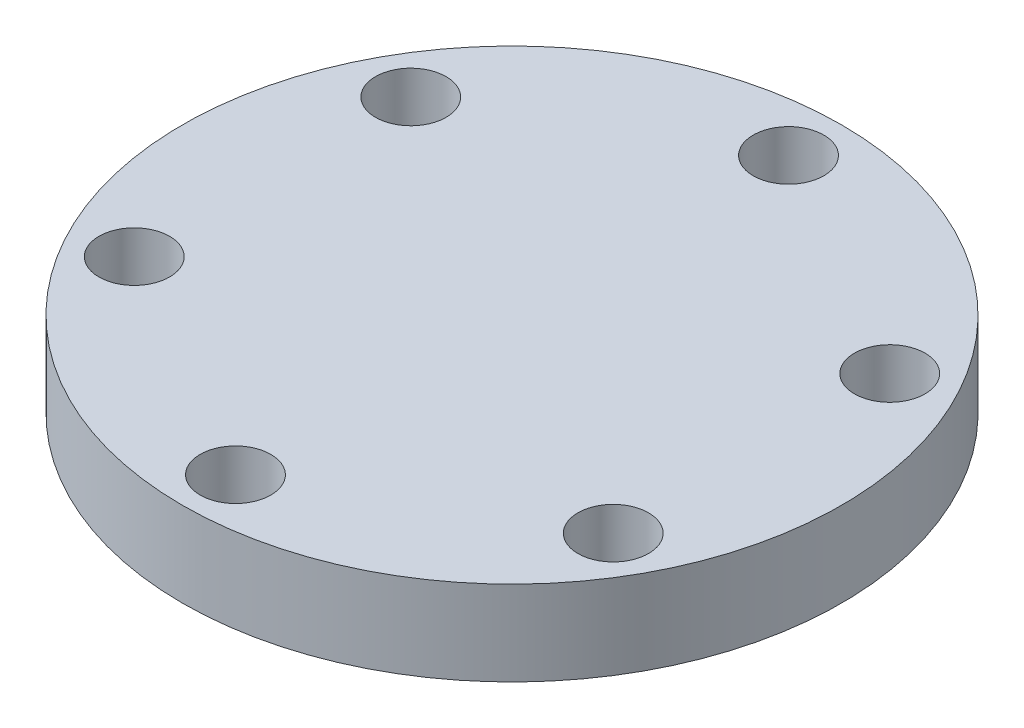
SolidWorks part; units mm, degrees
ref_plane "Front Plane" through (0, 0, 0) normal (0, 0, 1) x (1, 0, 0)
ref_plane "Top Plane" through (0, 0, 0) normal (0, 1, 0) x (1, 0, 0)
ref_plane "Right Plane" through (0, 0, 0) normal (1, 0, 0) x (0, 0, -1)
sketch "Sketch1" plane through (0, 0, 0) normal (0, 1, 0) x (1, 0, 0)
  circle A0 centre (0, 0) radius 7
  dimension "D1" = 14
extrude "Boss-Extrude1" add sketch "Sketch1" along normal blind 1.8
sketch "Sketch2" plane through (0, 0, 0) normal (0, -1, 0) x (1, 0, 0)
  circle A0 centre (0, 5.8737) radius 0.75
  dimension "D1" = 1.5
extrude "Cut-Extrude1" cut sketch "Sketch2" against normal through all
pattern_circular "CirPattern1" count 6 over 360 about axis through (0, 0, 0) along (0, 1, 0) of "Cut-Extrude1"
